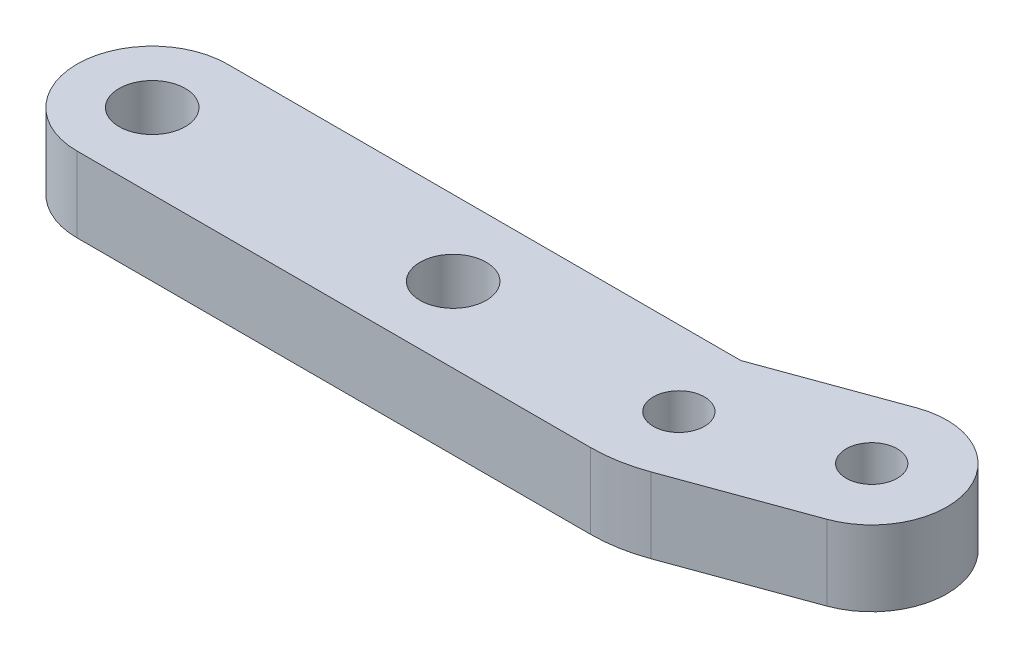
SolidWorks part; units mm, degrees
ref_plane "前视基准面" through (0, 0, 0) normal (0, 0, 1) x (1, 0, 0)
ref_plane "上视基准面" through (0, 0, 0) normal (0, 1, 0) x (1, 0, 0)
ref_plane "右视基准面" through (0, 0, 0) normal (1, 0, 0) x (0, 0, -1)
sketch "草图1" plane through (0, 0, 0) normal (0, 1, 0) x (1, 0, 0)
  line L0 (0, 0) -> (20, 0) construction
  line L1 (20, 0) -> (35, 0) construction
  line L2 (35, 0) -> (44.3969, 3.4202) construction
  line L3 (0, 5) -> (34.1184, 5)
  line L4 (34.1184, 5) -> (42.6868, 8.1187)
  line L5 (0, -5) -> (34.1184, -5)
  line L6 (35, 0) -> (34.1184, 5) construction
  line L7 (37.5386, -4.3969) -> (46.107, -1.2783)
  circle A0 centre (0, 0) radius 2.2
  circle A1 centre (20, 0) radius 2.2
  arc A2 (0, -5) -> (0, 5) centre (0, 0) cw
  arc A3 (34.1184, -5) -> (37.5386, -4.3969) centre (34.1184, 5) ccw
  arc A4 (42.6868, 8.1187) -> (46.107, -1.2783) centre (44.3969, 3.4202) cw
  circle A5 centre (35, 0) radius 1.7
  circle A6 centre (44.3969, 3.4202) radius 1.7
  dimension "D3" = 4.4
  dimension "D5" = 3.4
  dimension "D1" = 160
  dimension "D2" = 10
  dimension "D4" = 80
  dimension "D6" = 10
  dimension "D7" = 20
  dimension "D8" = 15
extrude "凸台-拉伸1" add sketch "草图1" along normal blind 5
